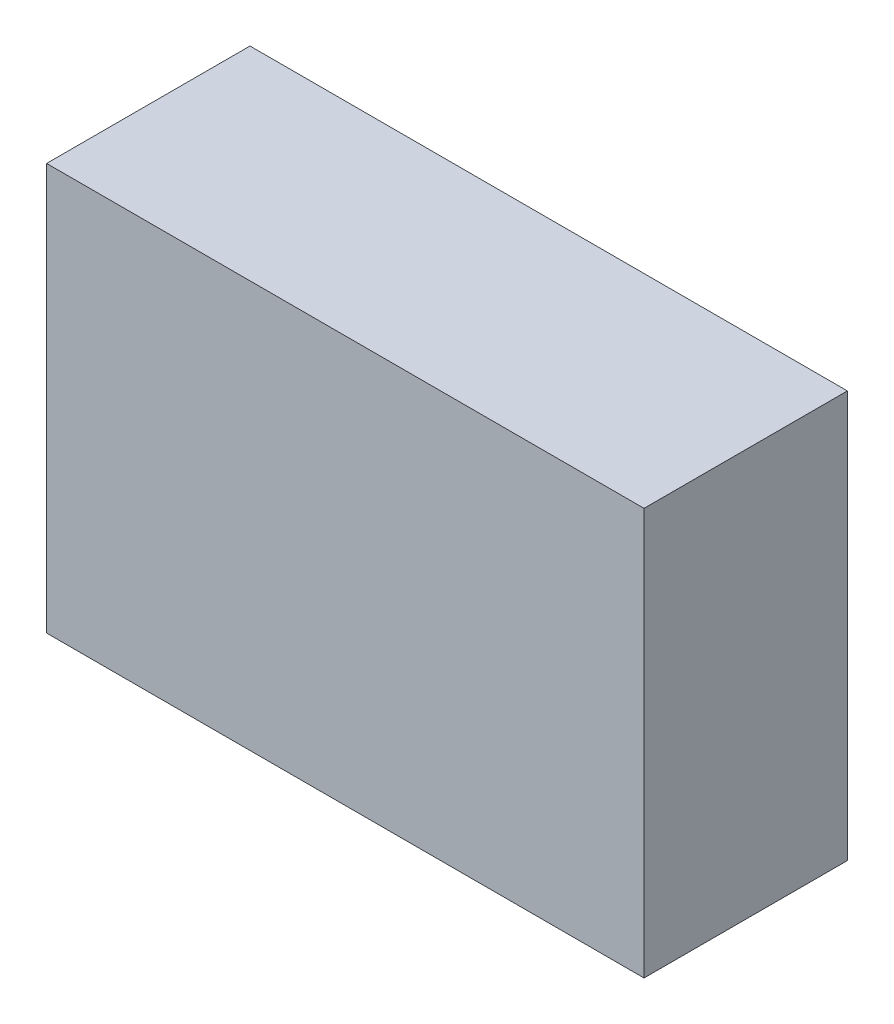
SolidWorks part; units mm, degrees
ref_plane "Front Plane" through (0, 0, 0) normal (0, 0, 1) x (1, 0, 0)
ref_plane "Top Plane" through (0, 0, 0) normal (0, 1, 0) x (1, 0, 0)
ref_plane "Right Plane" through (0, 0, 0) normal (1, 0, 0) x (0, 0, -1)
sketch "Sketch1" plane through (0, 0, 0) normal (0, 0, 1) x (1, 0, 0)
  line L1 (47, 32) -> (-47, 32)
  line L2 (47, 32) -> (47, -32)
  line L3 (47, -32) -> (-47, -32)
  line L4 (-47, 32) -> (-47, -32)
  line L5 (47, 32) -> (-47, -32) construction
  line L6 (47, -32) -> (-47, 32) construction
  point P0 (0, 0)
  dimension "D1" = 64
  dimension "D2" = 94
extrude "Boss-Extrude1" add sketch "Sketch1" along normal blind 32
